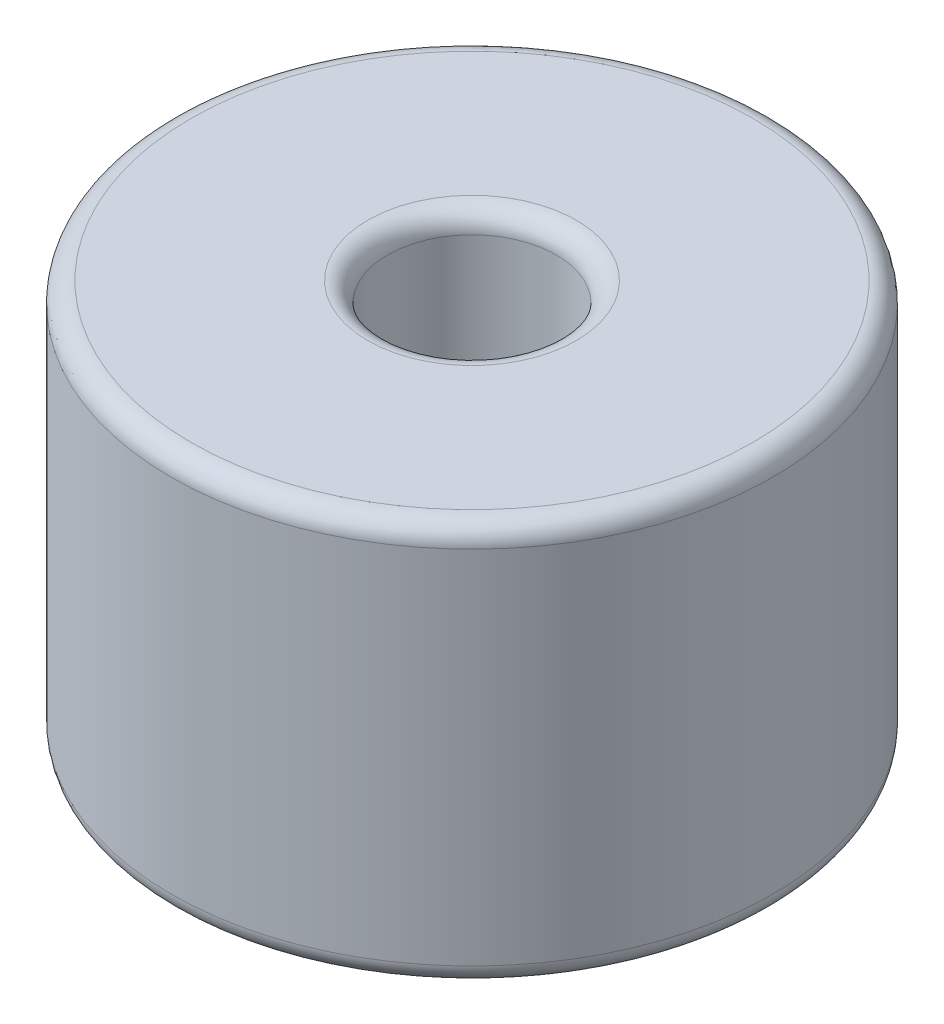
SolidWorks part; units mm, degrees
ref_plane "Front Plane" through (0, 0, 0) normal (0, 0, 1) x (1, 0, 0)
ref_plane "Top Plane" through (0, 0, 0) normal (0, 1, 0) x (1, 0, 0)
ref_plane "Right Plane" through (0, 0, 0) normal (1, 0, 0) x (0, 0, -1)
sketch "Sketch1" plane through (0, 0, 0) normal (0, 1, 0) x (1, 0, 0)
  circle A0 centre (0, 0) radius 2.1
  circle A1 centre (0, 0) radius 7.5
  dimension "D1" = 4.2
  dimension "D2" = 15
extrude "Boss-Extrude1" add sketch "Sketch1" along normal blind 10
fillet "Fillet1" radius 0.5 4 edges at (0, 0, 7.5) (0, 10, 7.5) (0, 0, 2.1) (0, 10, 2.1)
